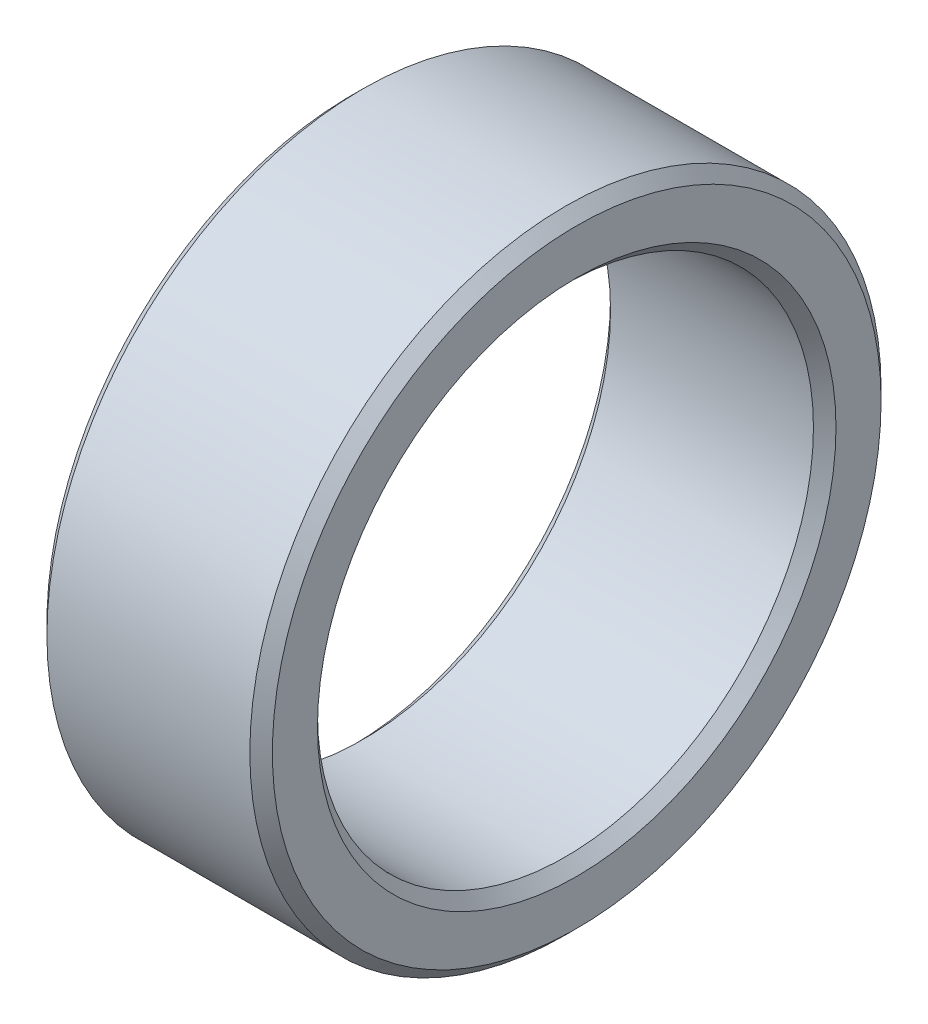
SolidWorks part; units mm, degrees
material "1023 Листовая углеродистая сталь (SS)"
ref_plane "Спереди" through (0, 0, 0) normal (0, 0, 1) x (1, 0, 0)
ref_plane "Сверху" through (0, 0, 0) normal (0, 1, 0) x (1, 0, 0)
ref_plane "Справа" through (0, 0, 0) normal (1, 0, 0) x (0, 0, -1)
sketch "Эскиз1" plane through (0, 0, 0) normal (0, 0, 1) x (1, 0, 0)
  line L0 (0, 11.5) -> (0.5, 11)
  line L1 (0.5, 11) -> (9.5, 11)
  line L2 (9.5, 11) -> (10, 11.5)
  line L3 (10, 11.5) -> (10, 13.5)
  line L4 (10, 13.5) -> (9.5, 14)
  line L5 (9.5, 14) -> (0.5, 14)
  line L6 (0.5, 14) -> (0, 13.5)
  line L7 (0, 13.5) -> (0, 11.5)
  line L8 (0, 0) -> (10, 0) construction
revolve "Повернуть1" add sketch "Эскиз1" angle 360 about L8
